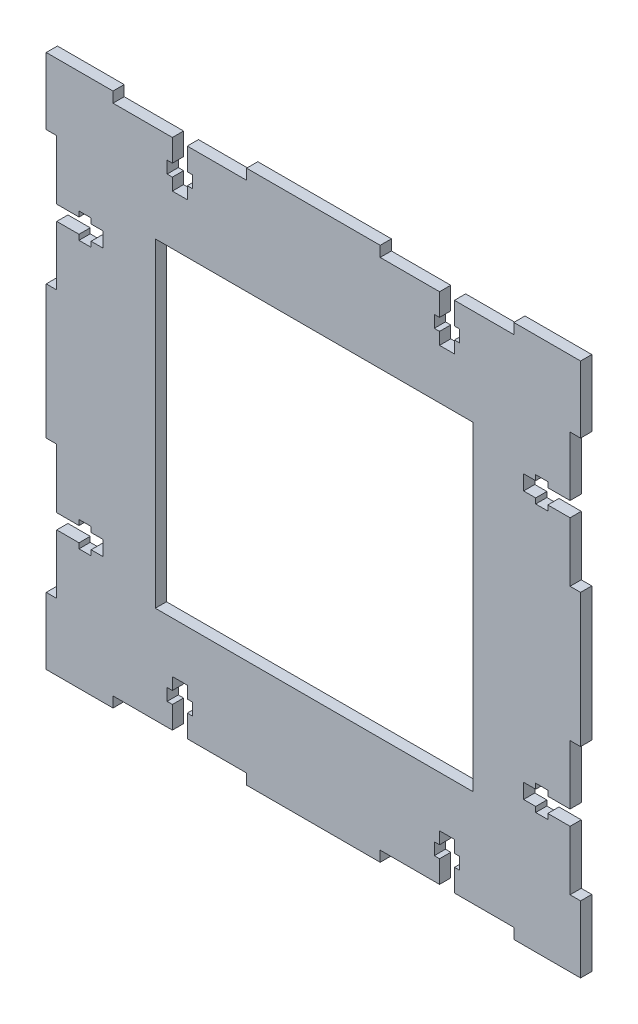
SolidWorks part; units mm, degrees
ref_plane "Front Plane" through (0, 0, 0) normal (0, 0, 1) x (1, 0, 0)
ref_plane "Top Plane" through (0, 0, 0) normal (0, 1, 0) x (1, 0, 0)
ref_plane "Right Plane" through (0, 0, 0) normal (1, 0, 0) x (0, 0, -1)
sketch "Sketch1" plane through (0, 0, 0) normal (0, 0, 1) x (1, 0, 0)
  line L0 (0, 154.3975) -> (0, 135.4704)
  line L1 (0, 135.4704) -> (2.9806, 135.4704)
  line L2 (2.9806, 135.4704) -> (2.9806, 118.6546)
  line L3 (2.9806, 118.6546) -> (9.2897, 118.6546)
  line L4 (9.2897, 118.6546) -> (9.2897, 120.1449)
  line L5 (9.2897, 120.1449) -> (12.7174, 120.1449)
  line L6 (12.7174, 120.1449) -> (12.7174, 118.6546)
  line L7 (12.7174, 118.6546) -> (16.1452, 118.6546)
  line L8 (16.1452, 118.6546) -> (16.1452, 114.432)
  line L9 (16.1452, 114.432) -> (12.7174, 114.432)
  line L10 (12.7174, 114.432) -> (12.7174, 112.9417)
  line L11 (12.7174, 112.9417) -> (9.2897, 112.9417)
  line L12 (9.2897, 112.9417) -> (9.2897, 114.432)
  line L13 (9.2897, 114.432) -> (2.9806, 114.432)
  line L14 (2.9806, 114.432) -> (2.9806, 97.6162)
  line L15 (2.9806, 97.6162) -> (0, 97.6162)
  line L16 (0, 97.6162) -> (0, 59.762)
  line L17 (0, 59.762) -> (2.9806, 59.762)
  line L18 (2.9806, 59.762) -> (2.9806, 42.9462)
  line L19 (2.9806, 42.9462) -> (9.2897, 42.9462)
  line L20 (9.2897, 42.9462) -> (9.2897, 44.4365)
  line L21 (9.2897, 44.4365) -> (12.7174, 44.4365)
  line L22 (12.7174, 44.4365) -> (12.7174, 42.9462)
  line L23 (12.7174, 42.9462) -> (16.1452, 42.9462)
  line L24 (16.1452, 42.9462) -> (16.1452, 38.7236)
  line L25 (16.1452, 38.7236) -> (12.7174, 38.7236)
  line L26 (12.7174, 38.7236) -> (12.7174, 37.2332)
  line L27 (12.7174, 37.2332) -> (9.2897, 37.2332)
  line L28 (9.2897, 37.2332) -> (9.2897, 38.7236)
  line L29 (9.2897, 38.7236) -> (2.9806, 38.7236)
  line L30 (2.9806, 38.7236) -> (2.9806, 21.9078)
  line L31 (2.9806, 21.9078) -> (0, 21.9078)
  line L32 (0, 21.9078) -> (0, 2.9806)
  line L33 (0, 2.9806) -> (18.9271, 2.9806)
  line L34 (18.9271, 2.9806) -> (18.9271, 5.9613)
  line L35 (18.9271, 5.9613) -> (35.7429, 5.9613)
  line L36 (35.7429, 5.9613) -> (35.7429, 12.2703)
  line L37 (35.7429, 12.2703) -> (34.2526, 12.2703)
  line L38 (34.2526, 12.2703) -> (34.2526, 15.6981)
  line L39 (34.2526, 15.6981) -> (35.7429, 15.6981)
  line L40 (35.7429, 15.6981) -> (35.7429, 19.1258)
  line L41 (35.7429, 19.1258) -> (39.9655, 19.1258)
  line L42 (39.9655, 19.1258) -> (39.9655, 15.6981)
  line L43 (39.9655, 15.6981) -> (41.4558, 15.6981)
  line L44 (41.4558, 15.6981) -> (41.4558, 12.2703)
  line L45 (41.4558, 12.2703) -> (39.9655, 12.2703)
  line L46 (39.9655, 12.2703) -> (39.9655, 5.9613)
  line L47 (39.9655, 5.9613) -> (56.7813, 5.9613)
  line L48 (56.7813, 5.9613) -> (56.7813, 2.9806)
  line L49 (56.7813, 2.9806) -> (94.6355, 2.9806)
  line L50 (94.6355, 2.9806) -> (94.6355, 5.9613)
  line L51 (94.6355, 5.9613) -> (111.4513, 5.9613)
  line L52 (111.4513, 5.9613) -> (111.4513, 12.2703)
  line L53 (111.4513, 12.2703) -> (109.961, 12.2703)
  line L54 (109.961, 12.2703) -> (109.961, 15.6981)
  line L55 (109.961, 15.6981) -> (111.4513, 15.6981)
  line L56 (111.4513, 15.6981) -> (111.4513, 19.1258)
  line L57 (111.4513, 19.1258) -> (115.6739, 19.1258)
  line L58 (115.6739, 19.1258) -> (115.6739, 15.6981)
  line L59 (115.6739, 15.6981) -> (117.1643, 15.6981)
  line L60 (117.1643, 15.6981) -> (117.1643, 12.2703)
  line L61 (117.1643, 12.2703) -> (115.6739, 12.2703)
  line L62 (115.6739, 12.2703) -> (115.6739, 5.9613)
  line L63 (115.6739, 5.9613) -> (132.4897, 5.9613)
  line L64 (132.4897, 5.9613) -> (132.4897, 2.9806)
  line L65 (132.4897, 2.9806) -> (151.4169, 2.9806)
  line L66 (151.4169, 2.9806) -> (151.4169, 21.9078)
  line L67 (151.4169, 21.9078) -> (148.4362, 21.9078)
  line L68 (148.4362, 21.9078) -> (148.4362, 38.7236)
  line L69 (148.4362, 38.7236) -> (142.1272, 38.7236)
  line L70 (142.1272, 38.7236) -> (142.1272, 37.2332)
  line L71 (142.1272, 37.2332) -> (138.6994, 37.2332)
  line L72 (138.6994, 37.2332) -> (138.6994, 38.7236)
  line L73 (138.6994, 38.7236) -> (135.2717, 38.7236)
  line L74 (135.2717, 38.7236) -> (135.2717, 42.9462)
  line L75 (135.2717, 42.9462) -> (138.6994, 42.9462)
  line L76 (138.6994, 42.9462) -> (138.6994, 44.4365)
  line L77 (138.6994, 44.4365) -> (142.1272, 44.4365)
  line L78 (142.1272, 44.4365) -> (142.1272, 42.9462)
  line L79 (142.1272, 42.9462) -> (148.4362, 42.9462)
  line L80 (148.4362, 42.9462) -> (148.4362, 59.762)
  line L81 (148.4362, 59.762) -> (151.4169, 59.762)
  line L82 (151.4169, 59.762) -> (151.4169, 97.6162)
  line L83 (151.4169, 97.6162) -> (148.4362, 97.6162)
  line L84 (148.4362, 97.6162) -> (148.4362, 114.432)
  line L85 (148.4362, 114.432) -> (142.1272, 114.432)
  line L86 (142.1272, 114.432) -> (142.1272, 112.9417)
  line L87 (142.1272, 112.9417) -> (138.6994, 112.9417)
  line L88 (138.6994, 112.9417) -> (138.6994, 114.432)
  line L89 (138.6994, 114.432) -> (135.2717, 114.432)
  line L90 (135.2717, 114.432) -> (135.2717, 118.6546)
  line L91 (135.2717, 118.6546) -> (138.6994, 118.6546)
  line L92 (138.6994, 118.6546) -> (138.6994, 120.1449)
  line L93 (138.6994, 120.1449) -> (142.1272, 120.1449)
  line L94 (142.1272, 120.1449) -> (142.1272, 118.6546)
  line L95 (142.1272, 118.6546) -> (148.4362, 118.6546)
  line L96 (148.4362, 118.6546) -> (148.4362, 135.4704)
  line L97 (148.4362, 135.4704) -> (151.4169, 135.4704)
  line L98 (151.4169, 135.4704) -> (151.4169, 154.3975)
  line L99 (151.4169, 154.3975) -> (132.4897, 154.3975)
  line L100 (132.4897, 154.3975) -> (132.4897, 151.4169)
  line L101 (132.4897, 151.4169) -> (115.6739, 151.4169)
  line L102 (115.6739, 151.4169) -> (115.6739, 145.1078)
  line L103 (115.6739, 145.1078) -> (117.1643, 145.1078)
  line L104 (117.1643, 145.1078) -> (117.1643, 141.6801)
  line L105 (117.1643, 141.6801) -> (115.6739, 141.6801)
  line L106 (115.6739, 141.6801) -> (115.6739, 138.2523)
  line L107 (115.6739, 138.2523) -> (111.4513, 138.2523)
  line L108 (111.4513, 138.2523) -> (111.4513, 141.6801)
  line L109 (111.4513, 141.6801) -> (109.961, 141.6801)
  line L110 (109.961, 141.6801) -> (109.961, 145.1078)
  line L111 (109.961, 145.1078) -> (111.4513, 145.1078)
  line L112 (111.4513, 145.1078) -> (111.4513, 151.4169)
  line L113 (111.4513, 151.4169) -> (94.6355, 151.4169)
  line L114 (94.6355, 151.4169) -> (94.6355, 154.3975)
  line L115 (94.6355, 154.3975) -> (56.7813, 154.3975)
  line L116 (56.7813, 154.3975) -> (56.7813, 151.4169)
  line L117 (56.7813, 151.4169) -> (39.9655, 151.4169)
  line L118 (39.9655, 151.4169) -> (39.9655, 145.1078)
  line L119 (39.9655, 145.1078) -> (41.4558, 145.1078)
  line L120 (41.4558, 145.1078) -> (41.4558, 141.6801)
  line L121 (41.4558, 141.6801) -> (39.9655, 141.6801)
  line L122 (39.9655, 141.6801) -> (39.9655, 138.2523)
  line L123 (39.9655, 138.2523) -> (35.7429, 138.2523)
  line L124 (35.7429, 138.2523) -> (35.7429, 141.6801)
  line L125 (35.7429, 141.6801) -> (34.2526, 141.6801)
  line L126 (34.2526, 141.6801) -> (34.2526, 145.1078)
  line L127 (34.2526, 145.1078) -> (35.7429, 145.1078)
  line L128 (35.7429, 145.1078) -> (35.7429, 151.4169)
  line L129 (35.7429, 151.4169) -> (18.9271, 151.4169)
  line L130 (18.9271, 151.4169) -> (18.9271, 154.3975)
  line L131 (18.9271, 154.3975) -> (0, 154.3975)
  line L132 (30.909, 124.1151) -> (30.909, 33.4689)
  line L133 (30.909, 33.4689) -> (120.8821, 33.4689)
  line L134 (120.8821, 124.1151) -> (120.8821, 33.4689)
  line L135 (30.909, 124.1151) -> (120.8821, 124.1151)
  line L628 (0, 78.6891) -> (151.4169, 78.6891) construction
  line L633 (75.7084, 154.3975) -> (75.7084, 2.9806) construction
  point P132 (0, 0)
  point P675 (75.7084, 78.6891)
extrude "Boss-Extrude1" add sketch "Sketch1" along normal blind 3.175
